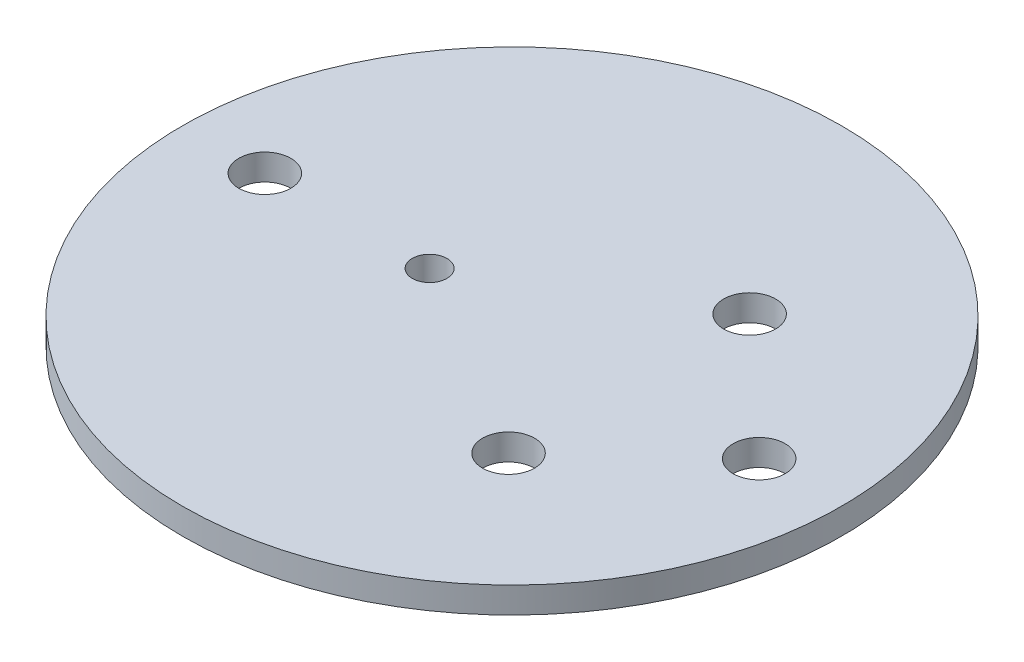
SolidWorks part; units mm, degrees
ref_plane "Front Plane" through (0, 0, 0) normal (0, 0, 1) x (1, 0, 0)
ref_plane "Top Plane" through (0, 0, 0) normal (0, 1, 0) x (1, 0, 0)
ref_plane "Right Plane" through (0, 0, 0) normal (1, 0, 0) x (0, 0, -1)
sketch "Sketch1" plane through (0, 0, 0) normal (0, 1, 0) x (1, 0, 0)
  line L0 (-28.5, 0) -> (28.5, 0) construction
  line L1 (13.5, 13.9) -> (13.5, -13.9) construction
  circle A0 centre (0, 0) radius 38
  circle A1 centre (28.5, 0) radius 3
  circle A2 centre (-28.5, 0) radius 3
  circle A3 centre (13.5, 13.9) radius 3
  circle A4 centre (13.5, -13.9) radius 3
  circle A5 centre (-28.5, 0) radius 6.25 construction
  circle A6 centre (13.5, 13.9) radius 12.5 construction
  circle A7 centre (13.5, -13.9) radius 12.5 construction
  circle A8 centre (28.5, 0) radius 6.25 construction
  circle A9 centre (-9.5, 0) radius 2
  circle A10 centre (-9.5, 0) radius 12.5 construction
  point P2 (13.5, 0)
  point P11 (0, 0)
  dimension "D1" = 76
  dimension "D3" = 6
  dimension "D4" = 13.9
  dimension "D5" = 6
  dimension "D6" = 12.5
  dimension "D7" = 25
  dimension "D9" = 4
  dimension "D10" = 25
  dimension "D2" = 57
  dimension "D8" = 13.5
  dimension "D11" = 9.5
extrude "Boss-Extrude1" add sketch "Sketch1" against normal blind 3
